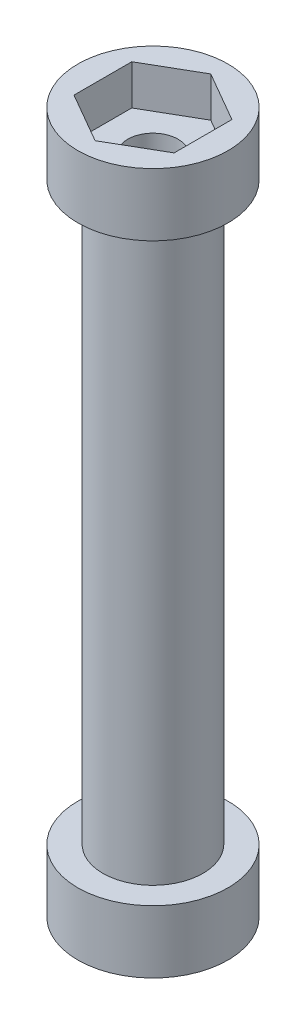
SolidWorks part; units mm, degrees
ref_plane "前视基准面" through (0, 0, 0) normal (0, 0, 1) x (1, 0, 0)
ref_plane "上视基准面" through (0, 0, 0) normal (0, 1, 0) x (1, 0, 0)
ref_plane "右视基准面" through (0, 0, 0) normal (1, 0, 0) x (0, 0, -1)
other "Configuration Table"
sketch "草图1" plane through (0, 0, 0) normal (0, 1, 0) x (1, 0, 0)
  circle A0 centre (0, 0) radius 2
  circle A1 centre (0, 0) radius 1
  dimension "D1" = 4
  dimension "D2" = 2
extrude "凸台-拉伸1" add sketch "草图1" along normal blind 28
sketch "草图2" plane through (0, 0, 0) normal (0, 1, 0) x (1, 0, 0)
  circle A0 centre (0, 0) radius 3
  circle A2 centre (0, 0) radius 2
  circle A3 centre (0, 0) radius 2
  dimension "D2" = 6
  dimension "D1" = 0
extrude "凸台-拉伸2" add sketch "草图2" along normal blind 2.5
sketch "草图3" plane through (0, 0, 0) normal (0, 1, 0) x (1, 0, 0)
  circle A1 centre (0, 0) radius 2
  circle A2 centre (0, 0) radius 2
  circle A3 centre (0, 0) radius 3
  circle A4 centre (0, 0) radius 3
  dimension "D1" = 0
  dimension "D2" = 0
extrude "凸台-拉伸3" add sketch "草图3" against normal blind 2.5 from surface at 28 starting at face at (0, 28, 2)
sketch "草图4" plane through (0, 0, 0) normal (0, 1, 0) x (1, 0, 0)
  circle A0 centre (0, 0) radius 1.6
  dimension "D1" = 3.2
extrude "切除-拉伸1" cut sketch "草图4" along normal blind 1.5
sketch "草图5" plane through (0, 0, 0) normal (0, 1, 0) x (1, 0, 0)
  line L1 (0, -2.3094) -> (2, -1.1547)
  line L2 (2, -1.1547) -> (2, 1.1547)
  line L3 (2, 1.1547) -> (0, 2.3094)
  line L4 (0, 2.3094) -> (-2, 1.1547)
  line L5 (-2, 1.1547) -> (-2, -1.1547)
  line L6 (-2, -1.1547) -> (0, -2.3094)
  circle A0 centre (0, 0) radius 2 construction
  dimension "D1" = 4
extrude "切除-拉伸2" cut sketch "草图5" against normal blind 1.6 from surface at 28 starting at face at (0, 28, 1)
